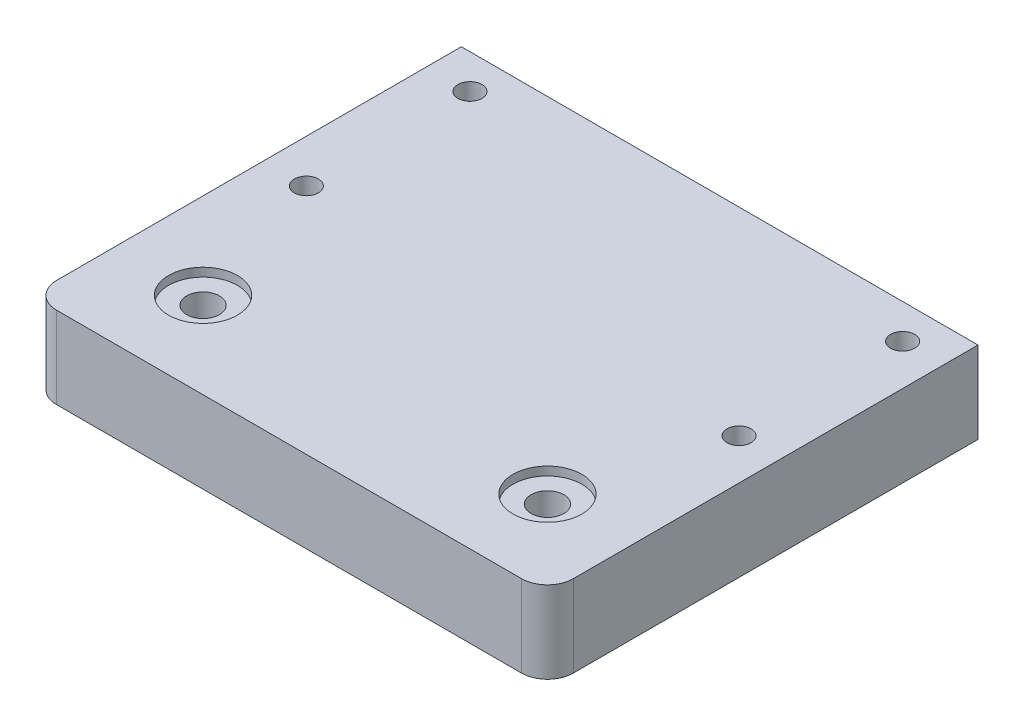
SolidWorks part; units mm, degrees
ref_plane "前视基准面" through (0, 0, 0) normal (0, 0, 1) x (1, 0, 0)
ref_plane "上视基准面" through (0, 0, 0) normal (0, 1, 0) x (1, 0, 0)
ref_plane "右视基准面" through (0, 0, 0) normal (1, 0, 0) x (0, 0, -1)
sketch "草图1" plane through (0, 0, 0) normal (0, 1, 0) x (1, 0, 0)
  line L1 (-30, 25) -> (30, 25)
  line L2 (-30, 25) -> (-30, -25)
  line L3 (-30, -25) -> (30, -25)
  line L4 (30, 25) -> (30, -25)
  line L5 (-30, 25) -> (30, -25) construction
  line L6 (-30, -25) -> (30, 25) construction
  point P0 (0, 0)
  dimension "D1" = 60
  dimension "D2" = 50
extrude "凸台-拉伸1" add sketch "草图1" along normal blind 9.5
fillet "圆角1" radius 3 2 edges at (-30, 4.75, 25) (30, 4.75, 25)
sketch "草图2" plane through (0, 9.5, 0) normal (0, 1, 0) x (1, 0, 0)
  line L0 (0, 0) -> (0, -25) construction
  line L1 (-27, -25) -> (27, -25) construction
  circle A0 centre (-20, -15) radius 4
  circle A1 centre (20, -15) radius 4
  dimension "D1" = 8
  dimension "D2" = 40
  dimension "D3" = 10
extrude "切除-拉伸1" cut sketch "草图2" against normal blind 1 contours A1 | A0
sketch "草图5" plane through (0, 9.5, 0) normal (0, 1, 0) x (1, 0, 0)
  circle A0 centre (-20, -15) radius 1.9
  circle A1 centre (20, -15) radius 1.9
  dimension "D1" = 3.8
extrude "切除-拉伸3" cut sketch "草图5" against normal through all
sketch "草图6" plane through (0, 0, 0) normal (0, -1, 0) x (1, 0, 0)
  circle A0 centre (-25, -21) radius 1.4
  circle A1 centre (-25, -2) radius 1.4
  circle A2 centre (25.25, -21) radius 1.4
  circle A3 centre (25.25, -2) radius 1.4
  dimension "D1" = 2.8
extrude "切除-拉伸4" cut sketch "草图6" against normal through all
sketch "草图7" plane through (0, 0, 0) normal (0, -1, 0) x (1, 0, 0)
  circle A0 centre (-20, 15) radius 4
  circle A1 centre (20, 15) radius 4
  circle A2 centre (25.25, -2) radius 3
  circle A3 centre (25.25, -21) radius 3
  circle A4 centre (-25, -21) radius 3
  circle A5 centre (-25, -2) radius 3
  dimension "D1" = 8
  dimension "D2" = 6
extrude "切除-拉伸5" cut sketch "草图7" against normal blind 4
